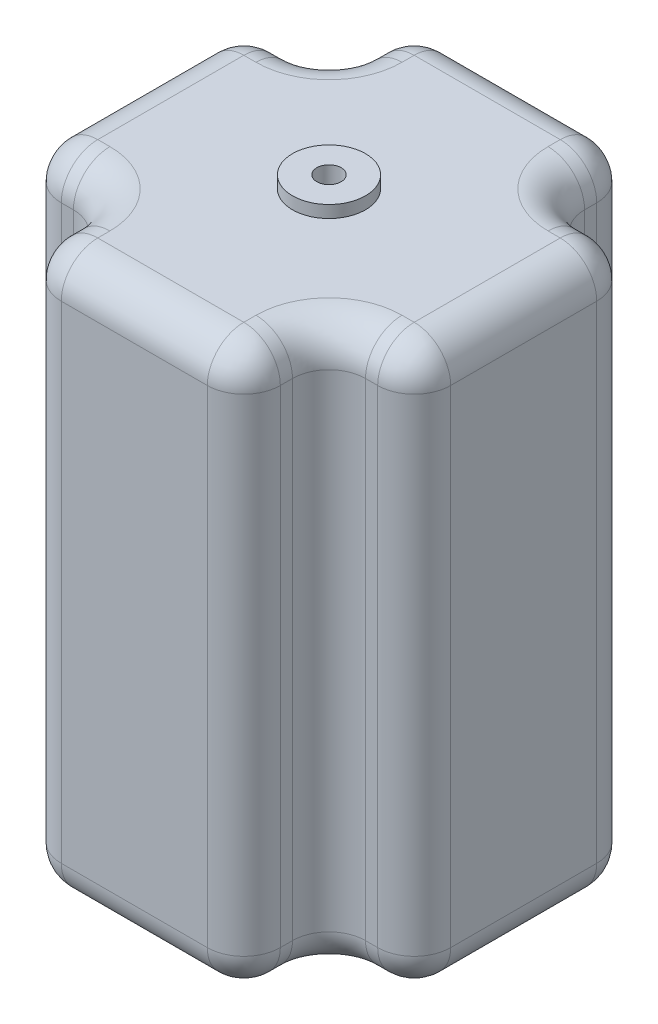
SolidWorks part; units mm, degrees
ref_plane "Front Plane" through (0, 0, 0) normal (0, 0, 1) x (1, 0, 0)
ref_plane "Top Plane" through (0, 0, 0) normal (0, 1, 0) x (1, 0, 0)
ref_plane "Right Plane" through (0, 0, 0) normal (1, 0, 0) x (0, 0, -1)
sketch "Sketch1" plane through (0, 0, 0) normal (0, 1, 0) x (1, 0, 0)
  line L0 (-9, 9) -> (-9, 16)
  line L1 (-9, -16) -> (9, -16)
  line L2 (-9, -16) -> (-9, -9)
  line L3 (-9, 16) -> (9, 16)
  line L4 (9, -16) -> (9, -9)
  line L5 (-9, -16) -> (9, 16) construction
  line L6 (-9, 16) -> (9, -16) construction
  line L7 (-16, -9) -> (-9, -9)
  line L8 (-16, -9) -> (-16, 9)
  line L9 (-16, 9) -> (-9, 9)
  line L10 (16, -9) -> (16, 9)
  line L11 (-16, -9) -> (16, 9) construction
  line L12 (-16, 9) -> (16, -9) construction
  line L13 (9, 9) -> (16, 9)
  line L14 (9, 9) -> (9, 16)
  line L15 (9, -9) -> (16, -9)
  point P0 (0, 0)
  point P6 (0, 0)
  dimension "D1" = 18
  dimension "D2" = 7
extrude "Boss-Extrude1" add sketch "Sketch1" along normal blind 46
fillet "Fillet1" radius 3 36 edges at (9, 23, 16) (-9, 23, 16) (-16, 0, 0) (-9, 0, 12.5) (0, 0, 16) (9, 0, 12.5) (-9, 0, -12.5) (-9, 23, -9) (-16, 23, -9) (-12.5, 0, -9) (-9, 23, -16) (0, 0, -16) (9, 23, -16) (9, 0, -12.5) (9, 23, -9) (12.5, 0, -9) (12.5, 46, -9) (9, 46, 12.5) (0, 46, 16) (-9, 46, 12.5) (-16, 46, 0) (-12.5, 46, -9) (-9, 46, -12.5) (0, 46, -16) (9, 46, -12.5) (-16, 23, 9) (-12.5, 46, 9) (-9, 23, 9) (-12.5, 0, 9) (16, 46, 0) (16, 23, -9) (16, 0, 0) (9, 23, 9) (12.5, 46, 9) (16, 23, 9) (12.5, 0, 9)
sketch "Sketch2" plane through (0, 46, 0) normal (0, 1, 0) x (1, 0, 0)
  circle A0 centre (0, 0) radius 3
extrude "Boss-Extrude2" add sketch "Sketch2" along normal blind 1
shell "Shell1" thickness 2
